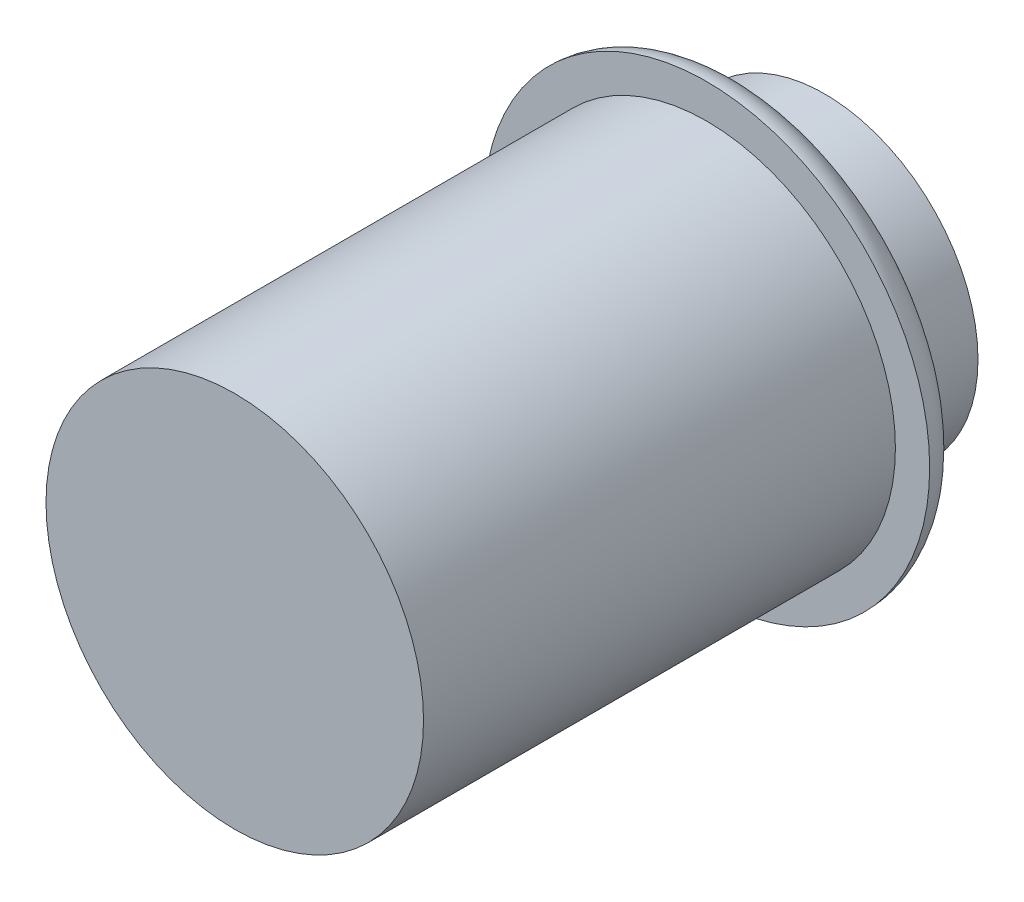
SolidWorks part; units mm, degrees
ref_plane "Front Plane" through (0, 0, 0) normal (0, 0, 1) x (1, 0, 0)
ref_plane "Top Plane" through (0, 0, 0) normal (0, 1, 0) x (1, 0, 0)
ref_plane "Right Plane" through (0, 0, 0) normal (1, 0, 0) x (0, 0, -1)
sketch "Sketch1" plane through (0, 0, 0) normal (0, 0, 1) x (1, 0, 0)
  circle A0 centre (0, 0) radius 8
  dimension "D1" = 16
extrude "Boss-Extrude1" add sketch "Sketch1" along normal blind 20
sketch "Sketch2" plane through (0, 0, 0) normal (0, 1, 0) x (1, 0, 0)
  line L0 (8, 0) -> (-8, 0) construction
  line L1 (9.4515, 0) -> (6.5485, 0)
  line L2 (0, 0) -> (0, 2.5601) construction
  arc A0 (6.5485, 0) -> (9.4515, 0) centre (8, 0) cw
revolve "Revolve1" add sketch "Sketch2" angle 360 about L2
sketch "Sketch3" plane through (0, 0, 0) normal (0, 0, -1) x (-1, 0, 0)
  circle A0 centre (0, 0) radius 6.5
  dimension "D1" = 13
extrude "Boss-Extrude2" add sketch "Sketch3" along normal blind 5
